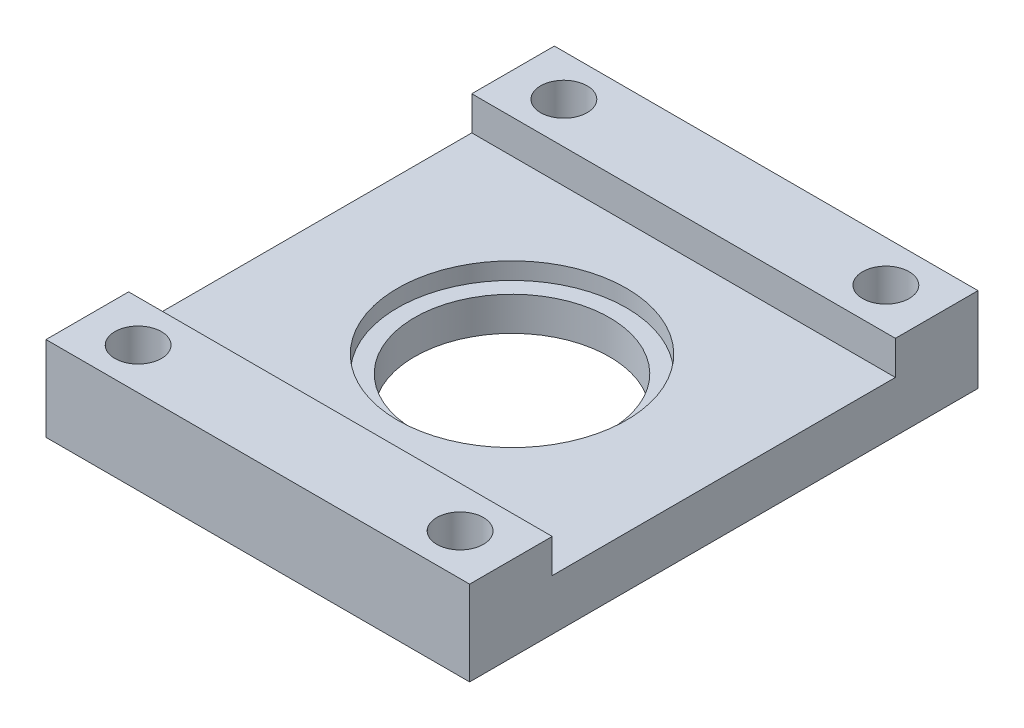
SolidWorks part; units mm, degrees
ref_plane "Front Plane" through (0, 0, 0) normal (0, 0, 1) x (1, 0, 0)
ref_plane "Top Plane" through (0, 0, 0) normal (0, 1, 0) x (1, 0, 0)
ref_plane "Right Plane" through (0, 0, 0) normal (1, 0, 0) x (0, 0, -1)
sketch "Sketch1" plane through (0, 0, 0) normal (0, 1, 0) x (1, 0, 0)
  line L1 (0, 0) -> (63.5, 0)
  line L2 (0, 0) -> (0, -76.2)
  line L3 (0, -76.2) -> (63.5, -76.2)
  line L4 (63.5, 0) -> (63.5, -76.2)
  dimension "D1" = 76.2
  dimension "D2" = 63.5
extrude "Boss-Extrude1" add sketch "Sketch1" along normal blind 12.7
sketch "Sketch2" plane through (0, 12.7, 0) normal (0, 1, 0) x (1, 0, 0)
  line L0 (0, 0) -> (0, -76.2) construction
  line L1 (0, -12.3825) -> (63.5, -12.3825)
  line L2 (0, -12.3825) -> (0, -63.8175)
  line L3 (0, -63.8175) -> (63.5, -63.8175)
  line L4 (63.5, -12.3825) -> (63.5, -63.8175)
  line L5 (63.5, -76.2) -> (63.5, 0) construction
  line L6 (63.5, 0) -> (0, 0) construction
  dimension "D1" = 51.435
  dimension "D2" = 12.3825
extrude "Cut-Extrude1" cut sketch "Sketch2" against normal blind 5.08
sketch "Sketch3" plane through (0, 7.62, 0) normal (0, 1, 0) x (1, 0, 0)
  circle A0 centre (31.75, -38.1) radius 14.605
  dimension "D1" = 29.21
extrude "Cut-Extrude2" cut sketch "Sketch3" against normal blind 7.62
sketch "Sketch4" plane through (0, 12.7, 0) normal (0, 1, 0) x (1, 0, 0)
  line L0 (0, 0) -> (0, -12.3825) construction
  line L1 (63.5, -12.3825) -> (63.5, 0) construction
  circle A0 centre (7.62, -6.1913) radius 3.4925
  circle A1 centre (55.88, -6.1913) radius 3.4925
  circle A2 centre (7.62, -70.0087) radius 3.4925
  circle A3 centre (55.88, -70.0087) radius 3.4925
  dimension "D1" = 6.985
  dimension "D2" = 6.985
  dimension "D3" = 7.62
  dimension "D4" = 7.62
  dimension "D5" = 6.985
  dimension "D6" = 6.985
extrude "Cut-Extrude4" cut sketch "Sketch4" against normal blind 12.7
sketch "Sketch6" plane through (0, 7.62, 0) normal (0, 1, 0) x (1, 0, 0)
  circle A0 centre (31.75, -38.1) radius 17.145
  dimension "D1" = 34.29
extrude "Cut-Extrude6" cut sketch "Sketch6" against normal blind 2.54
